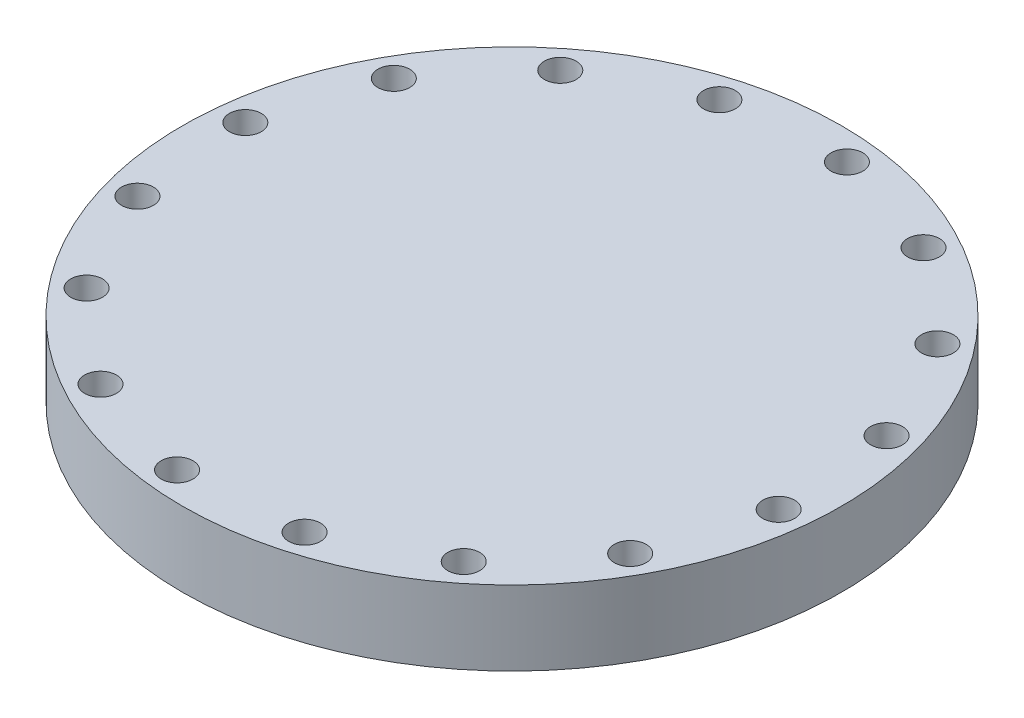
SolidWorks part; units mm, degrees
ref_plane "Front Plane" through (0, 0, 0) normal (0, 0, 1) x (1, 0, 0)
ref_plane "Top Plane" through (0, 0, 0) normal (0, 1, 0) x (1, 0, 0)
ref_plane "Right Plane" through (0, 0, 0) normal (1, 0, 0) x (0, 0, -1)
sketch "Sketch1" plane through (0, 0, 0) normal (0, 1, 0) x (1, 0, 0)
  circle A0 centre (0, 0) radius 25.8537
  dimension "D1" = 51.7074
extrude "Boss-Extrude1" add sketch "Sketch1" along normal mid plane 5.85
sketch "Sketch2" plane through (0, -2.925, 0) normal (0, -1, 0) x (1, 0, 0)
  arc A0 (22.0197, -5.6026) -> (23.6341, -7.5115) centre (22.8269, -6.557) ccw construction
  arc A1 (23.6341, -7.5115) -> (22.0197, -5.6026) centre (22.8269, -6.557) ccw construction
  arc A2 (22.7914, 3.632) -> (24.4058, 1.7231) centre (23.5986, 2.6776) ccw construction
  arc A3 (24.4058, 1.7231) -> (22.7914, 3.632) centre (23.5986, 2.6776) ccw construction
  arc A4 (17.7728, -13.839) -> (19.3873, -15.7478) centre (18.58, -14.7934) ccw construction
  arc A5 (19.3873, -15.7478) -> (17.7728, -13.839) centre (18.58, -14.7934) ccw construction
  arc A6 (10.6973, -19.8232) -> (12.3117, -21.732) centre (11.5045, -20.7776) ccw construction
  arc A7 (12.3117, -21.732) -> (10.6973, -19.8232) centre (11.5045, -20.7776) ccw construction
  arc A8 (1.8704, -22.6442) -> (3.4848, -24.553) centre (2.6776, -23.5986) ccw construction
  arc A9 (3.4848, -24.553) -> (1.8704, -22.6442) centre (2.6776, -23.5986) ccw construction
  arc A10 (-7.3642, -21.8725) -> (-5.7498, -23.7813) centre (-6.557, -22.8269) ccw construction
  arc A11 (-5.7498, -23.7813) -> (-7.3642, -21.8725) centre (-6.557, -22.8269) ccw construction
  arc A12 (-15.6006, -17.6256) -> (-13.9862, -19.5345) centre (-14.7934, -18.58) ccw construction
  arc A13 (-13.9862, -19.5345) -> (-15.6006, -17.6256) centre (-14.7934, -18.58) ccw construction
  arc A14 (-21.5848, -10.5501) -> (-19.9704, -12.459) centre (-20.7776, -11.5045) ccw construction
  arc A15 (-19.9704, -12.459) -> (-21.5848, -10.5501) centre (-20.7776, -11.5045) ccw construction
  arc A16 (-24.4058, -1.7231) -> (-22.7914, -3.632) centre (-23.5986, -2.6776) ccw construction
  arc A17 (-22.7914, -3.632) -> (-24.4058, -1.7231) centre (-23.5986, -2.6776) ccw construction
  arc A18 (-23.6341, 7.5115) -> (-22.0197, 5.6026) centre (-22.8269, 6.557) ccw construction
  arc A19 (-22.0197, 5.6026) -> (-23.6341, 7.5115) centre (-22.8269, 6.557) ccw construction
  arc A20 (-19.3873, 15.7478) -> (-17.7728, 13.839) centre (-18.58, 14.7934) ccw construction
  arc A21 (-17.7728, 13.839) -> (-19.3873, 15.7478) centre (-18.58, 14.7934) ccw construction
  arc A22 (-12.3117, 21.732) -> (-10.6973, 19.8232) centre (-11.5045, 20.7776) ccw construction
  arc A23 (-10.6973, 19.8232) -> (-12.3117, 21.732) centre (-11.5045, 20.7776) ccw construction
  arc A24 (-3.4848, 24.553) -> (-1.8704, 22.6442) centre (-2.6776, 23.5986) ccw construction
  arc A25 (-1.8704, 22.6442) -> (-3.4848, 24.553) centre (-2.6776, 23.5986) ccw construction
  arc A26 (5.7498, 23.7813) -> (7.3642, 21.8725) centre (6.557, 22.8269) ccw construction
  arc A27 (7.3642, 21.8725) -> (5.7498, 23.7813) centre (6.557, 22.8269) ccw construction
  arc A28 (19.9704, 12.459) -> (21.5848, 10.5501) centre (20.7776, 11.5045) ccw construction
  arc A29 (21.5848, 10.5501) -> (19.9704, 12.459) centre (20.7776, 11.5045) ccw construction
  arc A30 (13.9862, 19.5345) -> (15.6006, 17.6256) centre (14.7934, 18.58) ccw construction
  arc A31 (15.6006, 17.6256) -> (13.9862, 19.5345) centre (14.7934, 18.58) ccw construction
  arc A32 (22.0197, -5.6026) -> (23.6341, -7.5115) centre (22.8269, -6.557) ccw
  arc A33 (23.6341, -7.5115) -> (22.0197, -5.6026) centre (22.8269, -6.557) ccw
  arc A34 (22.7914, 3.632) -> (24.4058, 1.7231) centre (23.5986, 2.6776) ccw
  arc A35 (24.4058, 1.7231) -> (22.7914, 3.632) centre (23.5986, 2.6776) ccw
  arc A36 (17.7728, -13.839) -> (19.3873, -15.7478) centre (18.58, -14.7934) ccw
  arc A37 (19.3873, -15.7478) -> (17.7728, -13.839) centre (18.58, -14.7934) ccw
  arc A38 (10.6973, -19.8232) -> (12.3117, -21.732) centre (11.5045, -20.7776) ccw
  arc A39 (12.3117, -21.732) -> (10.6973, -19.8232) centre (11.5045, -20.7776) ccw
  arc A40 (1.8704, -22.6442) -> (3.4848, -24.553) centre (2.6776, -23.5986) ccw
  arc A41 (3.4848, -24.553) -> (1.8704, -22.6442) centre (2.6776, -23.5986) ccw
  arc A42 (-7.3642, -21.8725) -> (-5.7498, -23.7813) centre (-6.557, -22.8269) ccw
  arc A43 (-5.7498, -23.7813) -> (-7.3642, -21.8725) centre (-6.557, -22.8269) ccw
  arc A44 (-15.6006, -17.6256) -> (-13.9862, -19.5345) centre (-14.7934, -18.58) ccw
  arc A45 (-13.9862, -19.5345) -> (-15.6006, -17.6256) centre (-14.7934, -18.58) ccw
  arc A46 (-21.5848, -10.5501) -> (-19.9704, -12.459) centre (-20.7776, -11.5045) ccw
  arc A47 (-19.9704, -12.459) -> (-21.5848, -10.5501) centre (-20.7776, -11.5045) ccw
  arc A48 (-24.4058, -1.7231) -> (-22.7914, -3.632) centre (-23.5986, -2.6776) ccw
  arc A49 (-22.7914, -3.632) -> (-24.4058, -1.7231) centre (-23.5986, -2.6776) ccw
  arc A50 (-23.6341, 7.5115) -> (-22.0197, 5.6026) centre (-22.8269, 6.557) ccw
  arc A51 (-22.0197, 5.6026) -> (-23.6341, 7.5115) centre (-22.8269, 6.557) ccw
  arc A52 (-19.3873, 15.7478) -> (-17.7728, 13.839) centre (-18.58, 14.7934) ccw
  arc A53 (-17.7728, 13.839) -> (-19.3873, 15.7478) centre (-18.58, 14.7934) ccw
  arc A54 (-12.3117, 21.732) -> (-10.6973, 19.8232) centre (-11.5045, 20.7776) ccw
  arc A55 (-10.6973, 19.8232) -> (-12.3117, 21.732) centre (-11.5045, 20.7776) ccw
  arc A56 (-3.4848, 24.553) -> (-1.8704, 22.6442) centre (-2.6776, 23.5986) ccw
  arc A57 (-1.8704, 22.6442) -> (-3.4848, 24.553) centre (-2.6776, 23.5986) ccw
  arc A58 (5.7498, 23.7813) -> (7.3642, 21.8725) centre (6.557, 22.8269) ccw
  arc A59 (7.3642, 21.8725) -> (5.7498, 23.7813) centre (6.557, 22.8269) ccw
  arc A60 (19.9704, 12.459) -> (21.5848, 10.5501) centre (20.7776, 11.5045) ccw
  arc A61 (21.5848, 10.5501) -> (19.9704, 12.459) centre (20.7776, 11.5045) ccw
  arc A62 (13.9862, 19.5345) -> (15.6006, 17.6256) centre (14.7934, 18.58) ccw
  arc A63 (15.6006, 17.6256) -> (13.9862, 19.5345) centre (14.7934, 18.58) ccw
extrude "Cut-Extrude1" cut sketch "Sketch2" against normal through all
